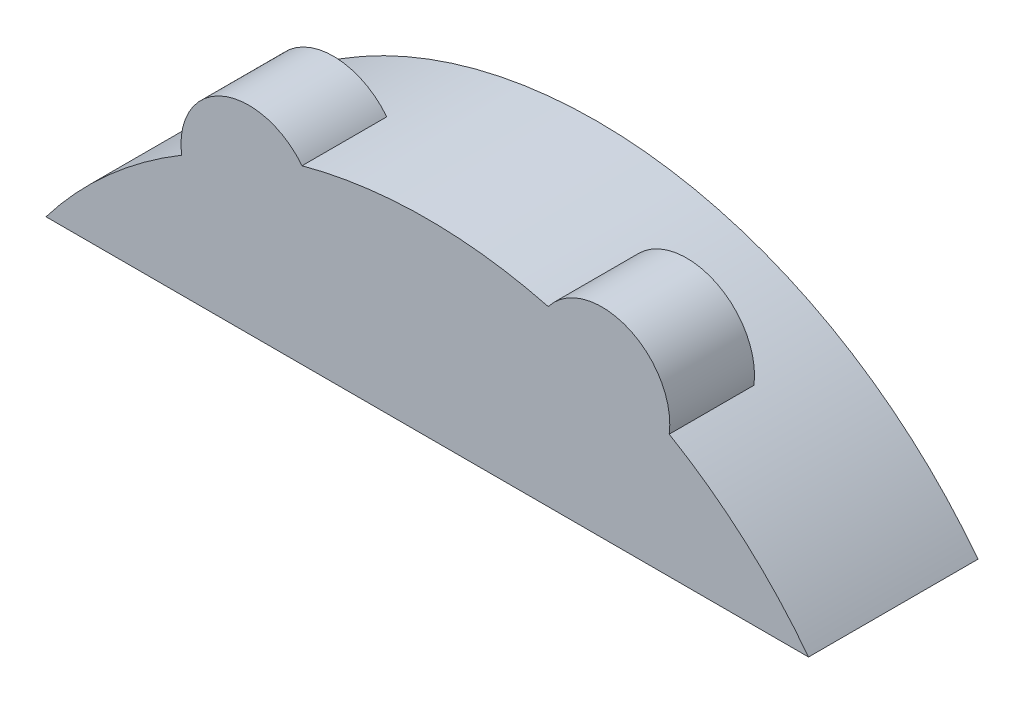
SolidWorks part; units mm, degrees
ref_plane "Front Plane" through (0, 0, 0) normal (0, 0, 1) x (1, 0, 0)
ref_plane "Top Plane" through (0, 0, 0) normal (0, 1, 0) x (1, 0, 0)
ref_plane "Right Plane" through (0, 0, 0) normal (1, 0, 0) x (0, 0, -1)
sketch "Sketch1" plane through (0, 0, 0) normal (0, 0, 1) x (1, 0, 0)
  line L0 (50, 35) -> (-40, 35)
  arc A0 (-40, 35) -> (50, 35) centre (5, 0.7217) cw
  point P0 (0, 0)
  dimension "D1" = 90
extrude "Boss-Extrude2" add sketch "Sketch1" against normal blind 20
sketch "Sketch3" plane through (0, 0, 0) normal (0, 0, 1) x (1, 0, 0)
  line L0 (-23.9953, 49.2941) -> (-9.782, 55.3248)
  line L2 (19.2744, 55.4597) -> (33.5561, 49.5535)
  arc A1 (-9.782, 55.3248) -> (-23.9953, 49.2941) centre (-16.069, 50.3777) ccw
  arc A6 (50, 35) -> (-40, 35) centre (5, 0.7217) ccw construction
  arc A7 (19.2744, 55.4597) -> (33.5561, 49.5535) centre (25.624, 50.5932) cw
extrude "Boss-Extrude3" add sketch "Sketch3" against normal blind 10
